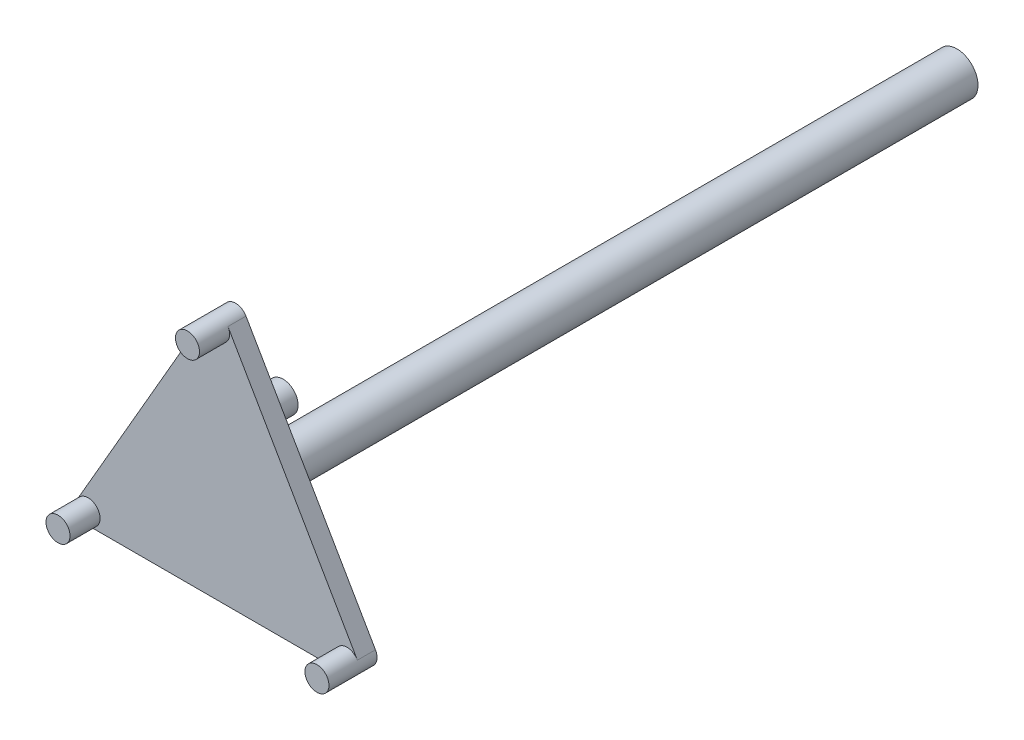
SolidWorks part; units mm, degrees
ref_plane "Front Plane" through (0, 0, 0) normal (0, 0, 1) x (1, 0, 0)
ref_plane "Top Plane" through (0, 0, 0) normal (0, 1, 0) x (1, 0, 0)
ref_plane "Right Plane" through (0, 0, 0) normal (1, 0, 0) x (0, 0, -1)
sketch "Sketch1" plane through (0, 0, 0) normal (0, 0, 1) x (1, 0, 0)
  line L1 (23.2679, -11.4338) -> (1.7321, 25.8675)
  line L2 (-1.7321, 25.8675) -> (-23.2679, -11.4338)
  line L3 (-21.5359, -14.4338) -> (21.5359, -14.4338)
  circle A0 centre (0, 0) radius 14.4338 construction
  arc A1 (-23.2679, -11.4338) -> (-21.5359, -14.4338) centre (-21.5359, -12.4338) ccw
  arc A2 (23.2679, -11.4338) -> (21.5359, -14.4338) centre (21.5359, -12.4338) cw
  arc A3 (1.7321, 25.8675) -> (-1.7321, 25.8675) centre (0, 24.8675) ccw
  point P8 (-25, -14.4338)
  point P11 (25, -14.4338)
  dimension "D2" = 2
  dimension "D3" = 2
  dimension "D4" = 2
  dimension "D1" = 50
extrude "Boss-Extrude1" add sketch "Sketch1" along normal blind 3
sketch "Sketch2" plane through (0, 0, 0) normal (0, 0, -1) x (-1, 0, 0)
  circle A0 centre (0, 0) radius 3.5
  dimension "D1" = 7
extrude "Boss-Extrude2" add sketch "Sketch2" along normal blind 10
sketch "Sketch3" plane through (0, 0, 3) normal (0, 0, 1) x (1, 0, 0)
  circle A0 centre (0, 24.8675) radius 2
  circle A1 centre (21.5359, -12.4338) radius 2
  circle A2 centre (-21.5359, -12.4338) radius 2
  dimension "D1" = 4
  dimension "D2" = 4
  dimension "D3" = 4
extrude "Boss-Extrude3" add sketch "Sketch3" along normal blind 5
sketch "Sketch4" plane through (0, 0, 0) normal (0, 0, -1) x (-1, 0, 0)
  line L0 (21.5359, -14.4338) -> (-21.5359, -14.4338) construction
  circle A0 centre (-10, -11.4338) radius 2.5
  dimension "D1" = 3
  dimension "D2" = 10
extrude "Boss-Extrude4" add sketch "Sketch4" along normal blind 3
pattern_circular "CirPattern1" count 3 every 120 about axis through (0, 0, 0) along (0, 0, 1) of "Boss-Extrude4"
sketch "Sketch5" plane through (0, 0, -10) normal (0, 0, -1) x (-1, 0, 0)
  circle A0 centre (0, 0) radius 3.5
  dimension "D1" = 7
extrude "Boss-Extrude6" add sketch "Sketch5" along normal blind 110
